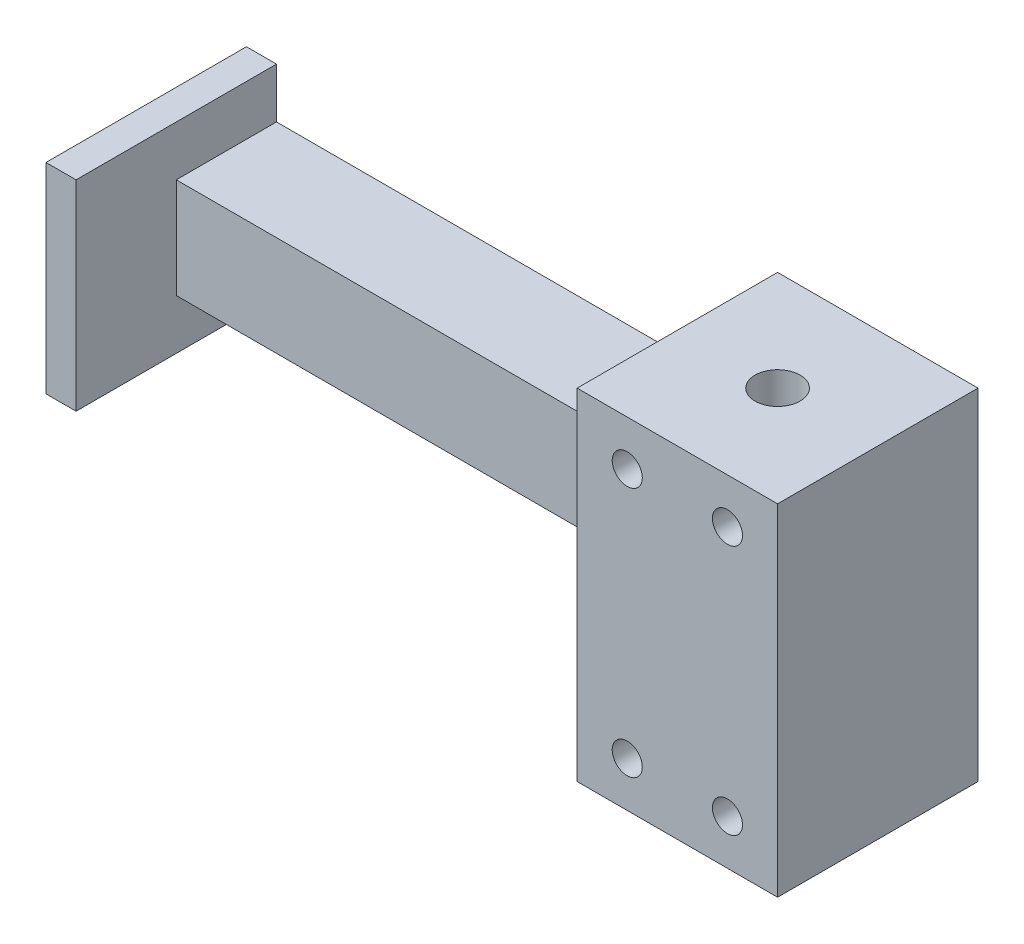
SolidWorks part; units mm, degrees
ref_plane "Front Plane" through (0, 0, 0) normal (0, 0, 1) x (1, 0, 0)
ref_plane "Top Plane" through (0, 0, 0) normal (0, 1, 0) x (1, 0, 0)
ref_plane "Right Plane" through (0, 0, 0) normal (1, 0, 0) x (0, 0, -1)
sketch "Main" plane through (0, 0, 0) normal (0, 0, 1) x (1, 0, 0)
  line L1 (0, 17) -> (20, 17)
  line L2 (0, 17) -> (0, -17)
  line L3 (0, -17) -> (20, -17)
  line L4 (20, 17) -> (20, -17)
  circle A0 centre (5, 12.5) radius 1.5
  circle A1 centre (15, 12.5) radius 1.5
  circle A2 centre (5, -12.5) radius 1.5
  circle A3 centre (15, -12.5) radius 1.5
  point P13 (0, 0)
  point P14 (0, 0)
  point P15 (0, 0)
  point P16 (0, 0)
  dimension "D3" = 3
  dimension "D1" = 34
  dimension "D2" = 20
  dimension "D4" = 4.5
  dimension "D5" = 4.5
  dimension "D6" = 5
  dimension "D7" = 5
extrude "Main Extrusion" add sketch "Main" along normal blind 20
sketch "Esquisse2" plane through (0, -17, 0) normal (0, -1, 0) x (1, 0, 0)
  line L0 (0, 20) -> (20, 20) construction
  line L1 (20, 20) -> (20, 0) construction
  circle A0 centre (10, 10) radius 2.25
  point P2 (0, 0)
  point P5 (10, 20)
  point P6 (0, 0)
  point P9 (20, 10)
  dimension "D1" = 4.5
extrude "Enlèv. mat.-Extru.1" cut sketch "Esquisse2" against normal through all
sketch "Esquisse3" plane through (0, 0, 0) normal (-1, 0, 0) x (0, 0, 1)
  line L0 (0, 17) -> (0, -17) construction
  line L1 (10, 5) -> (0, 5)
  line L2 (10, 5) -> (10, -5)
  line L3 (10, -5) -> (0, -5)
  line L4 (0, 5) -> (0, -5)
  point P6 (0, 0)
  dimension "D1" = 10
  dimension "D2" = 10
extrude "Boss.-Extru.3" add sketch "Esquisse3" along normal blind 50
sketch "Esquisse4" plane through (-50, 0, 0) normal (-1, 0, 0) x (0, 0, 1)
  line L0 (10, 5) -> (0, 5) construction
  line L1 (0, 10) -> (20, 10)
  line L2 (0, 10) -> (0, -10)
  line L3 (0, -10) -> (20, -10)
  line L4 (20, 10) -> (20, -10)
  line L5 (0, 5) -> (0, -5) construction
  point P7 (5, 5)
  point P8 (0, 0)
  point P11 (0, 0)
  dimension "D1" = 20
  dimension "D2" = 20
extrude "Boss.-Extru.4" add sketch "Esquisse4" along normal blind 3
